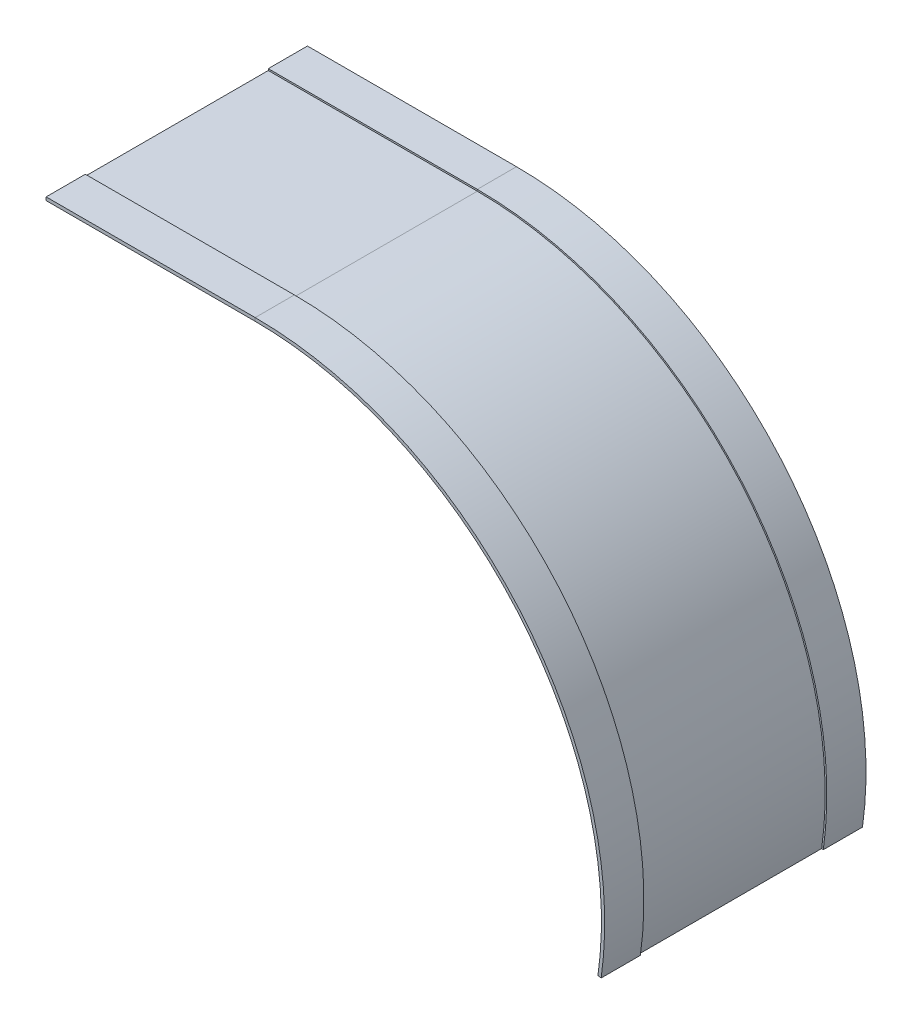
SolidWorks part; units mm, degrees
material "SHEET STEEL"
ref_plane "Front Plane" through (0, 0, 0) normal (0, 0, 1) x (1, 0, 0)
ref_plane "Top Plane" through (0, 0, 0) normal (0, 1, 0) x (1, 0, 0)
ref_plane "Right Plane" through (0, 0, 0) normal (1, 0, 0) x (0, 0, -1)
sketch "Sketch2" plane through (0, 0, 0) normal (0, 0, 1) x (1, 0, 0)
  line L0 (0, -105.6481) -> (0, 105.6481) construction
  line L1 (0, 160.0676) -> (-101.6, 160.0676)
  arc A0 (0, 160.0676) -> (166.5816, -32.0199) centre (0, -8.2074) cw
  dimension "D1" = 101.6
  dimension "D2" = 168.275
  dimension "D3" = 23.8125
ref_plane "Plane1" through (-101.6, 0, 0) normal (1, 0, 0) x (0, 0, -1)
sketch "Sketch3" plane through (-101.6, 0, 0) normal (1, 0, 0) x (0, 0, -1)
  line L0 (0, 160.0676) -> (-50000, 160.0676) construction
  line L1 (0, 160.0676) -> (0, -49839.9324) construction
  line L2 (63.5, 160.0676) -> (-63.5, 160.0676)
  line L3 (-63.5, 160.0676) -> (-63.5, 161.6551)
  line L4 (-63.5, 161.6551) -> (-44.45, 161.6551)
  line L5 (-44.45, 161.6551) -> (-44.45, 160.8614)
  line L6 (-44.45, 160.8614) -> (44.45, 160.8614)
  line L7 (44.45, 160.8614) -> (44.45, 161.6551)
  line L8 (44.45, 161.6551) -> (63.5, 161.6551)
  line L9 (63.5, 161.6551) -> (63.5, 160.0676)
  dimension "D1" = 19.05
  dimension "D2" = 127
  dimension "D3" = 0.7937
  dimension "D4" = 1.5875
sweep "Sweep1" add profiles "Sketch3" path "Sketch2"
